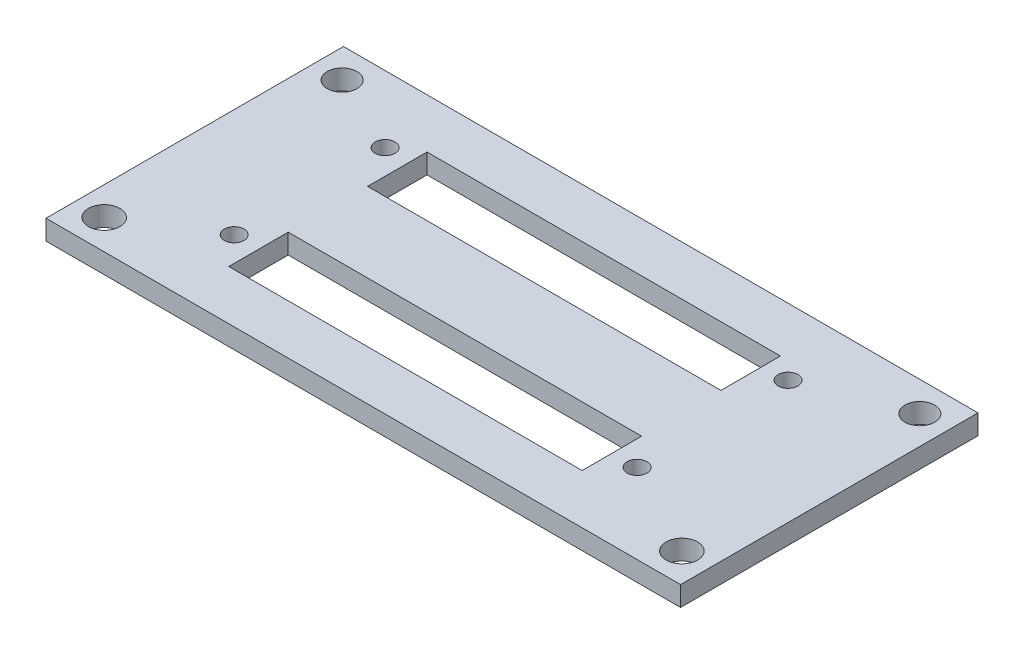
SolidWorks part; units mm, degrees
ref_plane "Front Plane" through (0, 0, 0) normal (0, 0, 1) x (1, 0, 0)
ref_plane "Top Plane" through (0, 0, 0) normal (0, 1, 0) x (1, 0, 0)
ref_plane "Right Plane" through (0, 0, 0) normal (1, 0, 0) x (0, 0, -1)
sketch "Sketch2" plane through (0, 0, 0) normal (0, 1, 0) x (1, 0, 0)
  line L0 (0, 0) -> (0, -15) construction
  line L1 (32, -15) -> (-32, -15)
  line L2 (32, -15) -> (32, 15)
  line L3 (32, 15) -> (-32, 15)
  line L4 (-32, -15) -> (-32, 15)
  line L5 (32, -15) -> (-32, 15) construction
  line L6 (32, 15) -> (-32, -15) construction
  circle A0 centre (-29.13, -12) radius 1.5893
  circle A1 centre (-29.1341, 12) radius 1.5
  circle A2 centre (29.13, -12) radius 1.5893
  circle A3 centre (29.1341, 12) radius 1.5
  point P0 (0, 0)
  dimension "D3" = 3
  dimension "D1" = 30
  dimension "D2" = 64
  dimension "D4" = 3
  dimension "D5" = 24
  dimension "D6" = 2.87
extrude "Boss-Extrude1" add sketch "Sketch2" along normal blind 2
sketch "Sketch3" plane through (0, 2, 0) normal (0, 1, 0) x (1, 0, 0)
  line L0 (-32, -15) -> (32, -15) construction
  line L1 (17.0719, -4) -> (-18.5686, -4)
  line L2 (17.0719, -4) -> (17.0719, -10)
  line L3 (17.0719, -10) -> (-18.5686, -10)
  line L4 (-18.5686, -4) -> (-18.5686, -10)
  line L5 (17.0719, -4) -> (-18.5686, -10) construction
  line L6 (17.0719, -10) -> (-18.5686, -4) construction
  line L7 (0, 0) -> (32, 0) construction
  line L8 (32, -15) -> (32, 15) construction
  line L9 (17.0719, 4) -> (17.0719, 10)
  line L10 (17.0719, 4) -> (-18.5686, 4)
  line L11 (-18.5686, 4) -> (-18.5686, 10)
  line L12 (17.0719, 10) -> (-18.5686, 10)
  circle A0 centre (-21.0686, 8.2672) radius 1
  circle A1 centre (19.5714, 8.2672) radius 1
  circle A2 centre (19.5714, -6.9528) radius 1
  circle A3 centre (-21.0686, -6.9528) radius 1
  point P8 (-0.7483, -7)
  point P13 (17.0719, -7)
  dimension "D2" = 2.5
  dimension "D1" = 2.5
  dimension "D3" = 6
  dimension "D4" = 5
extrude "Cut-Extrude1" cut sketch "Sketch3" against normal blind 2
